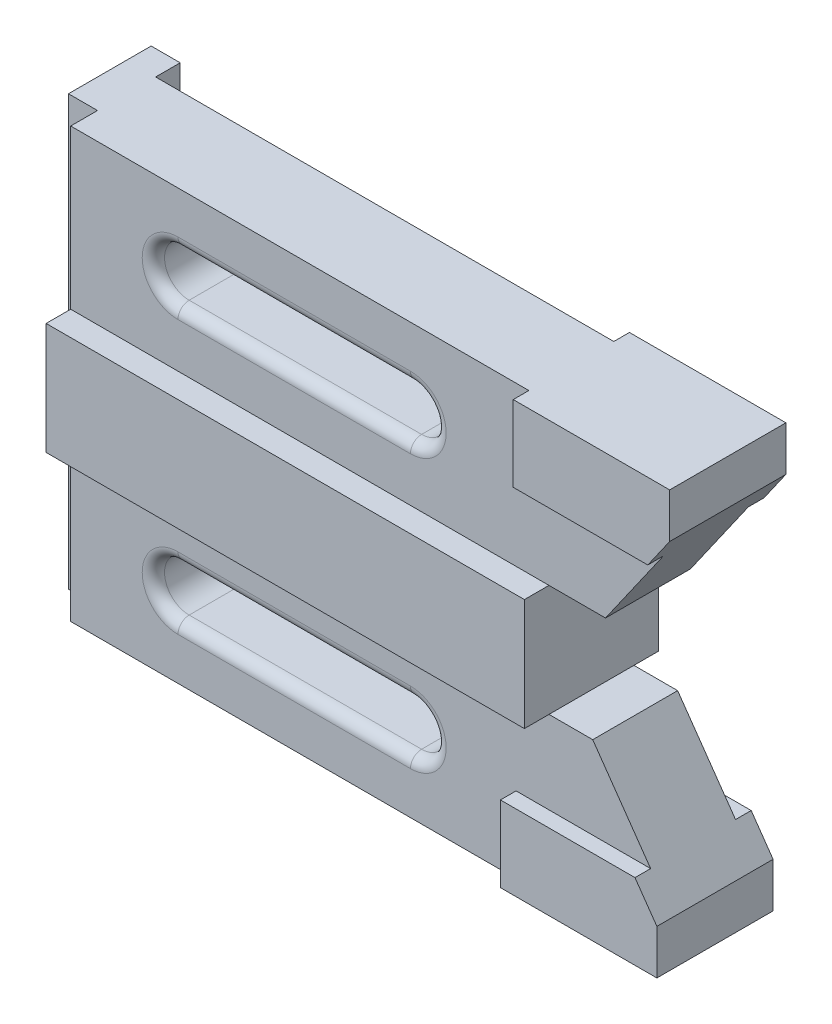
SolidWorks part; units mm, degrees
material "Alliage 1060"
ref_plane "Plan de face" through (0, 0, 0) normal (0, 0, 1) x (1, 0, 0)
ref_plane "Plan de dessus" through (0, 0, 0) normal (0, 1, 0) x (1, 0, 0)
ref_plane "Plan de droite" through (0, 0, 0) normal (1, 0, 0) x (0, 0, -1)
sketch "Esquisse1" plane through (0, 0, 0) normal (0, 0, 1) x (1, 0, 0)
  line L0 (-35.5636, 1.3888) -> (108.4364, 1.3888)
  line L1 (108.4364, 1.3888) -> (108.4364, -8.6112)
  line L2 (108.4364, -8.6112) -> (90.5811, -34.1112)
  line L3 (90.5811, -34.1112) -> (77.9364, -34.1112)
  line L4 (77.9364, -34.1112) -> (77.9364, -59.1112)
  line L5 (77.9364, -59.1112) -> (87.7211, -59.1112)
  line L6 (87.7211, -59.1112) -> (105.5764, -84.6112)
  line L7 (105.5764, -84.6112) -> (105.5764, -94.6112)
  line L8 (105.5764, -94.6112) -> (-35.5636, -94.6112)
  line L9 (-35.5636, -94.6112) -> (-35.5636, 1.3888)
  line L10 (105.5764, -84.6112) -> (46.2708, -84.6112) construction
  line L11 (108.4364, -8.6112) -> (55.3391, -8.6112) construction
  line L12 (-5.0636, -16.1112) -> (46.9364, -16.1112)
  line L13 (-5.0636, -10.6112) -> (46.9364, -10.6112)
  line L14 (-5.0636, -21.6112) -> (46.9364, -21.6112)
  line L15 (-5.0636, -71.6112) -> (46.9364, -71.6112)
  line L16 (-5.0636, -82.6112) -> (46.9364, -82.6112)
  arc A0 (46.9364, -10.6112) -> (46.9364, -21.6112) centre (46.9364, -16.1112) cw
  arc A1 (-5.0636, -21.6112) -> (-5.0636, -10.6112) centre (-5.0636, -16.1112) cw
  arc A2 (46.9364, -71.6112) -> (46.9364, -82.6112) centre (46.9364, -77.1112) cw
  arc A3 (-5.0636, -82.6112) -> (-5.0636, -71.6112) centre (-5.0636, -77.1112) cw
  dimension "D1" = 144
  dimension "D2" = 96
  dimension "D3" = 10
  dimension "D4" = 10
  dimension "D5" = 30.5
  dimension "D6" = 35.5
  dimension "D7" = 35.5
  dimension "D8" = 55
  dimension "D9" = 55
  dimension "D10" = 52
  dimension "D11" = 17.5
  dimension "D12" = 17.5
  dimension "D13" = 52
  dimension "D14" = 30.5
  dimension "D15" = 30.5
extrude "Boss.-Extru.1" add sketch "Esquisse1" along normal blind 30 contours L9 L8 L7 L6 L5 L4 L3 L2 L1 L0 L14 A1 L13 A0 L16 A3 L15 A2
sketch "Esquisse3" plane through (0, 0, 30) normal (0, 0, 1) x (1, 0, 0)
  line L0 (-29.0636, 1.3888) -> (-29.0636, -94.6112)
  line L1 (-35.5636, 1.3888) -> (108.4364, 1.3888) construction
  line L2 (105.5764, -94.6112) -> (-35.5636, -94.6112) construction
  line L3 (-29.0636, -94.6112) -> (-35.5636, -94.6112)
  line L4 (-35.5636, -94.6112) -> (-35.5636, 1.3888)
  line L5 (-35.5636, -94.6112) -> (-35.5636, 1.3888) construction
  line L6 (-35.5636, 1.3888) -> (-29.0636, 1.3888)
  dimension "D1" = 6.5
extrude "Enlèv. mat.-Extru.1" cut sketch "Esquisse3" against normal blind 11.5
sketch "Esquisse4" plane through (0, 0, 30) normal (0, 0, 1) x (1, 0, 0)
  line L0 (105.5764, -94.6112) -> (70.5764, -94.6112)
  line L1 (105.5764, -94.6112) -> (-29.0636, -94.6112) construction
  line L2 (70.5764, -94.6112) -> (70.5764, -77.6112)
  line L3 (70.5764, -77.6112) -> (100.675, -77.6112)
  line L4 (87.7211, -59.1112) -> (105.5764, -84.6112) construction
  line L5 (100.675, -77.6112) -> (105.5764, -84.6112)
  line L6 (105.5764, -84.6112) -> (105.5764, -94.6112) construction
  line L7 (105.5764, -84.6112) -> (105.5764, -94.6112)
  line L8 (77.9364, -59.1112) -> (-29.0636, -59.1112)
  line L9 (-29.0636, -94.6112) -> (-29.0636, 1.3888) construction
  line L10 (-29.0636, -59.1112) -> (-29.0636, -34.1112)
  line L11 (-29.0636, -34.1112) -> (77.9364, -34.1112)
  line L12 (77.9364, -34.1112) -> (77.9364, -59.1112)
  line L13 (108.4364, 1.3888) -> (108.4364, -8.6112)
  line L14 (108.4364, 1.3888) -> (108.4364, -8.6112) construction
  line L15 (108.4364, -8.6112) -> (103.535, -15.6112)
  line L16 (108.4364, -8.6112) -> (90.5811, -34.1112) construction
  line L17 (103.535, -15.6112) -> (73.4364, -15.6112)
  line L18 (73.4364, -15.6112) -> (73.4364, 1.3888)
  line L19 (-29.0636, 1.3888) -> (108.4364, 1.3888) construction
  line L20 (73.4364, 1.3888) -> (108.4364, 1.3888)
  line L21 (-29.0636, -59.1112) -> (-29.0636, -94.6112)
  line L22 (-29.0636, -94.6112) -> (70.5764, -94.6112)
  line L23 (70.5764, -77.6112) -> (100.675, -77.6112)
  line L24 (-29.0636, -94.6112) -> (70.5764, -94.6112)
  line L25 (70.5764, -77.6112) -> (100.675, -77.6112)
  line L26 (87.7211, -59.1112) -> (-29.0636, -59.1112)
  line L27 (-29.0636, 1.3888) -> (-29.0636, -34.1112)
  line L28 (77.9364, -34.1112) -> (90.5811, -34.1112)
  line L29 (90.5811, -34.1112) -> (103.535, -15.6112)
  line L30 (73.4364, -15.6112) -> (73.4364, 1.3888)
  line M15 (-29.0636, 1.3888) -> (-29.0636, -94.6112)
  line M16 (-29.0636, -94.6112) -> (105.5764, -94.6112)
  line M18 (105.5764, -84.6112) -> (87.7211, -59.1112)
  line M19 (87.7211, -59.1112) -> (77.9364, -59.1112)
  line M21 (77.9364, -34.1112) -> (90.5811, -34.1112)
  line M22 (90.5811, -34.1112) -> (108.4364, -8.6112)
  line M24 (108.4364, 1.3888) -> (-29.0636, 1.3888)
  line M25 (46.9364, -21.6112) -> (-5.0636, -21.6112)
  arc M26 (-5.0636, -21.6112) -> (-5.0636, -10.6112) centre (-5.0636, -16.1112) cw
  line M27 (-5.0636, -10.6112) -> (46.9364, -10.6112)
  arc M28 (46.9364, -10.6112) -> (46.9364, -21.6112) centre (46.9364, -16.1112) cw
  line M29 (46.9364, -82.6112) -> (-5.0636, -82.6112)
  arc M30 (-5.0636, -82.6112) -> (-5.0636, -71.6112) centre (-5.0636, -77.1112) cw
  line M31 (-5.0636, -71.6112) -> (46.9364, -71.6112)
  arc M32 (46.9364, -71.6112) -> (46.9364, -82.6112) centre (46.9364, -77.1112) cw
  dimension "D1" = 35
  dimension "D2" = 17
  dimension "D3" = 35
  dimension "D4" = 17
extrude "Enlèv. mat.-Extru.2" cut sketch "Esquisse4" against normal blind 5.5 contours L17 L18 L11 M24 M15 M21 M22 M28 M25 M26 M27 | L8 L2 L3 M19 M15 M16 M18 M32 M29 M30 M31
sketch "Esquisse5" plane through (0, 0, 0) normal (0, 0, -1) x (-1, 0, 0)
  line L0 (-87.7211, -59.1112) -> (-77.9364, -59.1112) construction
  line L1 (-77.9364, -59.1112) -> (29.0636, -59.1112) construction
  line L2 (29.0636, -59.1112) -> (29.0636, -94.6112) construction
  line L3 (29.0636, -94.6112) -> (-70.5764, -94.6112) construction
  line L4 (-70.5764, -94.6112) -> (-70.5764, -77.6112) construction
  line L5 (-70.5764, -77.6112) -> (-100.675, -77.6112) construction
  line L6 (-100.675, -77.6112) -> (-87.7211, -59.1112) construction
  line L7 (-103.535, -15.6112) -> (-73.4364, -15.6112) construction
  line L8 (-73.4364, -15.6112) -> (-73.4364, 1.3888) construction
  line L9 (-73.4364, 1.3888) -> (29.0636, 1.3888) construction
  line L10 (29.0636, 1.3888) -> (29.0636, -34.1112) construction
  line L11 (29.0636, -34.1112) -> (-77.9364, -34.1112) construction
  line L12 (-77.9364, -34.1112) -> (-90.5811, -34.1112) construction
  line L13 (-90.5811, -34.1112) -> (-103.535, -15.6112) construction
  line L14 (-73.4364, -15.6112) -> (-73.4364, 1.3888) construction
  line L15 (-87.7211, -59.1112) -> (-77.9364, -59.1112)
  line L16 (-77.9364, -59.1112) -> (29.0636, -59.1112)
  line L17 (29.0636, -59.1112) -> (29.0636, -94.6112)
  line L18 (29.0636, -94.6112) -> (-70.5764, -94.6112)
  line L19 (-70.5764, -94.6112) -> (-70.5764, -77.6112)
  line L20 (-70.5764, -77.6112) -> (-100.675, -77.6112)
  line L21 (-100.675, -77.6112) -> (-87.7211, -59.1112)
  line L22 (-103.535, -15.6112) -> (-73.4364, -15.6112)
  line L23 (-73.4364, -15.6112) -> (-73.4364, 1.3888)
  line L24 (-73.4364, 1.3888) -> (29.0636, 1.3888)
  line L25 (29.0636, 1.3888) -> (29.0636, -34.1112)
  line L26 (29.0636, -34.1112) -> (-77.9364, -34.1112)
  line L27 (-77.9364, -34.1112) -> (-90.5811, -34.1112)
  line L28 (-90.5811, -34.1112) -> (-103.535, -15.6112)
  line L29 (-73.4364, -15.6112) -> (-73.4364, 1.3888)
  line M2 (35.5636, 1.3888) -> (-108.4364, 1.3888)
  line M4 (-108.4364, -8.6112) -> (-90.5811, -34.1112)
  line M5 (-90.5811, -34.1112) -> (-77.9364, -34.1112)
  line M7 (-77.9364, -59.1112) -> (-87.7211, -59.1112)
  line M8 (-87.7211, -59.1112) -> (-105.5764, -84.6112)
  line M10 (-105.5764, -94.6112) -> (35.5636, -94.6112)
  line M11 (5.0636, -21.6112) -> (-46.9364, -21.6112)
  arc M12 (-46.9364, -21.6112) -> (-46.9364, -10.6112) centre (-46.9364, -16.1112) cw
  line M13 (-46.9364, -10.6112) -> (5.0636, -10.6112)
  arc M14 (5.0636, -10.6112) -> (5.0636, -21.6112) centre (5.0636, -16.1112) cw
  line M15 (5.0636, -82.6112) -> (-46.9364, -82.6112)
  arc M16 (-46.9364, -82.6112) -> (-46.9364, -71.6112) centre (-46.9364, -77.1112) cw
  line M17 (-46.9364, -71.6112) -> (5.0636, -71.6112)
  arc M18 (5.0636, -71.6112) -> (5.0636, -82.6112) centre (5.0636, -77.1112) cw
extrude "Enlèv. mat.-Extru.3" cut sketch "Esquisse5" against normal blind 5.5 contours L26 L25 L23 L22 M2 M4 M5 M14 M11 M12 M13 | L20 L19 L17 L16 M10 M7 M8 M18 M15 M16 M17
sketch "Esquisse6" plane through (0, 0, 0) normal (0, 0, -1) x (-1, 0, 0)
  line L0 (-103.535, -15.6112) -> (-73.4364, -15.6112) construction
  line L1 (-73.4364, -15.6112) -> (-73.4364, 1.3888) construction
  line L2 (-73.4364, 1.3888) -> (-108.4364, 1.3888) construction
  line L3 (-108.4364, 1.3888) -> (-108.4364, -8.6112) construction
  line L4 (-108.4364, -8.6112) -> (-103.535, -15.6112) construction
  line L5 (-70.5764, -77.6112) -> (-100.675, -77.6112) construction
  line L6 (-100.675, -77.6112) -> (-105.5764, -84.6112) construction
  line L7 (-105.5764, -84.6112) -> (-105.5764, -94.6112) construction
  line L8 (-105.5764, -94.6112) -> (-70.5764, -94.6112) construction
  line L9 (-70.5764, -94.6112) -> (-70.5764, -77.6112) construction
  line L10 (-103.535, -15.6112) -> (-73.4364, -15.6112)
  line L11 (-73.4364, -15.6112) -> (-73.4364, 1.3888)
  line L12 (-73.4364, 1.3888) -> (-108.4364, 1.3888)
  line L13 (-108.4364, 1.3888) -> (-108.4364, -8.6112)
  line L14 (-108.4364, -8.6112) -> (-103.535, -15.6112)
  line L15 (-70.5764, -77.6112) -> (-100.675, -77.6112)
  line L16 (-100.675, -77.6112) -> (-105.5764, -84.6112)
  line L17 (-105.5764, -84.6112) -> (-105.5764, -94.6112)
  line L18 (-105.5764, -94.6112) -> (-70.5764, -94.6112)
  line L19 (-70.5764, -94.6112) -> (-70.5764, -77.6112)
extrude "Enlèv. mat.-Extru.4" cut sketch "Esquisse6" against normal blind 2
sketch "Esquisse7" plane through (0, 0, 30) normal (0, 0, 1) x (1, 0, 0)
  line L0 (73.4364, -15.6112) -> (103.535, -15.6112) construction
  line L1 (103.535, -15.6112) -> (108.4364, -8.6112) construction
  line L2 (108.4364, -8.6112) -> (108.4364, 1.3888) construction
  line L3 (108.4364, 1.3888) -> (73.4364, 1.3888) construction
  line L4 (73.4364, 1.3888) -> (73.4364, -15.6112) construction
  line L5 (100.675, -77.6112) -> (70.5764, -77.6112) construction
  line L6 (70.5764, -77.6112) -> (70.5764, -94.6112) construction
  line L7 (70.5764, -94.6112) -> (105.5764, -94.6112) construction
  line L8 (105.5764, -94.6112) -> (105.5764, -84.6112) construction
  line L9 (105.5764, -84.6112) -> (100.675, -77.6112) construction
  line L10 (73.4364, -15.6112) -> (103.535, -15.6112)
  line L11 (103.535, -15.6112) -> (108.4364, -8.6112)
  line L12 (108.4364, -8.6112) -> (108.4364, 1.3888)
  line L13 (108.4364, 1.3888) -> (73.4364, 1.3888)
  line L14 (73.4364, 1.3888) -> (73.4364, -15.6112)
  line L15 (100.675, -77.6112) -> (70.5764, -77.6112)
  line L16 (70.5764, -77.6112) -> (70.5764, -94.6112)
  line L17 (70.5764, -94.6112) -> (105.5764, -94.6112)
  line L18 (105.5764, -94.6112) -> (105.5764, -84.6112)
  line L19 (105.5764, -84.6112) -> (100.675, -77.6112)
extrude "Enlèv. mat.-Extru.5" cut sketch "Esquisse7" against normal blind 2 contours L10 L11 L12 L13 L14 | L15 L16 L17 L18 L19
fillet "Congé2" radius 2.5 4 edges at (-10.5636, -16.1112, 24.5) (52.4364, -16.1112, 24.5) (20.9364, -21.6112, 24.5) (20.9364, -10.6112, 24.5)
fillet "Congé3" radius 2.5 4 edges at (-10.5636, -77.1112, 24.5) (20.9364, -82.6112, 24.5) (52.4364, -77.1112, 24.5) (20.9364, -71.6112, 24.5)
fillet "Congé4" radius 2.5 4 edges at (-10.5636, -16.1112, 5.5) (20.9364, -10.6112, 5.5) (52.4364, -16.1112, 5.5) (20.9364, -21.6112, 5.5)
fillet "Congé5" radius 2.5 4 edges at (-10.5636, -77.1112, 5.5) (20.9364, -71.6112, 5.5) (52.4364, -77.1112, 5.5) (20.9364, -82.6112, 5.5)
equation "\"A\" = 144"
equation "\"B\" = 52"
equation "\"C\" = 55"
equation "\"D9@Esquisse1\"=\"C\""
equation "\"D8@Esquisse1\"=\"C\""
equation "\"D10@Esquisse1\"=\"B\""
equation "\"D13@Esquisse1\"=\"B\""
equation "\"D1@Esquisse1\"=\"A\""
